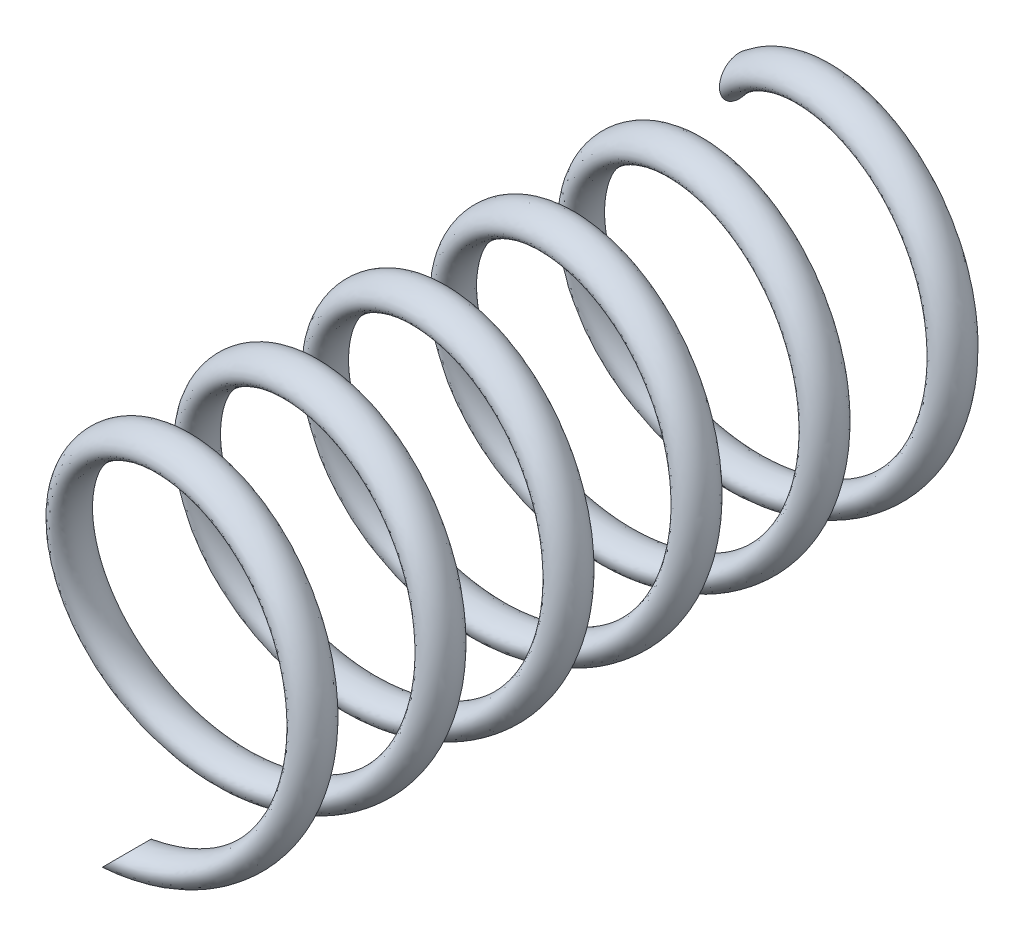
SolidWorks part; units mm, degrees
ref_plane "Front Plane" through (0, 0, 0) normal (0, 0, 1) x (1, 0, 0)
ref_plane "Top Plane" through (0, 0, 0) normal (0, 1, 0) x (1, 0, 0)
ref_plane "Right Plane" through (0, 0, 0) normal (1, 0, 0) x (0, 0, -1)
sketch "Sketch4" plane through (0, 0, 0) normal (0, 0, 1) x (1, 0, 0)
  circle A0 centre (0, 0) radius 9.5
  dimension "D1" = 19
curve "Helix/Spiral1" pitch 8 height 45 turns 5.625
ref_plane "Plane1" through (-6.7175, 0, 0) normal (1, 0, 0) x (0, 0, -1)
sketch "Sketch5" plane through (-6.7175, 0, 0) normal (1, 0, 0) x (0, 0, -1)
  circle A0 centre (0, 6.7175) radius 1.25
  spline S0 degree 3 poles (0, 6.7175) (-0.1656, 7.5913) (-0.5005, 9.0079) (-0.9999, 9.7466) (-1.5, 9.0055) (-2, 6.8924) (-2.5, 3.7302) (-3, 0) (-3.5, -3.7301) (-4, -6.8924) (-4.5, -9.0054) (-5, -9.7473) (-5.5, -9.0054) (-6, -6.8924) (-6.6667, -2.6761) (-7.3333, 2.6761) (-8, 6.8924) (-8.5, 9.0054) (-9, 9.7473) (-9.5, 9.0054) (-10, 6.8924) (-10.6667, 2.6761) (-11.3333, -2.6761) (-12, -6.8924) (-12.5, -9.0054) (-13, -9.7473) (-13.5, -9.0054) (-14, -6.8924) (-14.6667, -2.6761) (-15.3333, 2.6761) (-16, 6.8924) (-16.5, 9.0054) (-17, 9.7473) (-17.5, 9.0054) (-18, 6.8924) (-18.6667, 2.6761) (-19.3333, -2.6761) (-20, -6.8924) (-20.5, -9.0054) (-21, -9.7473) (-21.5, -9.0054) (-22, -6.8924) (-22.6667, -2.6761) (-23.3333, 2.6761) (-24, 6.8924) (-24.5, 9.0054) (-25, 9.7473) (-25.5, 9.0054) (-26, 6.8924) (-26.6667, 2.6761) (-27.3333, -2.6761) (-28, -6.8924) (-28.5, -9.0054) (-29, -9.7473) (-29.5, -9.0054) (-30, -6.8924) (-30.6667, -2.6761) (-31.3333, 2.6761) (-32, 6.8924) (-32.5, 9.0054) (-33, 9.7473) (-33.5, 9.0054) (-34, 6.8924) (-34.6667, 2.6761) (-35.3333, -2.6761) (-36, -6.8924) (-36.5, -9.0054) (-37, -9.7473) (-37.5, -9.0054) (-38, -6.8924) (-38.6667, -2.6761) (-39.3333, 2.6761) (-40, 6.8924) (-40.5, 9.0054) (-41, 9.7473) (-41.5, 9.0054) (-42, 6.8924) (-42.5, 3.7301) (-43, 0) (-43.5, -3.7301) (-44.0001, -6.8924) (-44.4995, -9.0054) (-44.8344, -9.5) (-45, -9.5) knots 0 0 0 0 0.011111 0.022222 0.033333 0.044444 0.055556 0.066667 0.077778 0.088889 0.1 0.111111 0.122222 0.133333 0.144444 0.166667 0.177778 0.188889 0.2 0.211111 0.222222 0.233333 0.255556 0.266667 0.277778 0.288889 0.3 0.311111 0.322222 0.344444 0.355556 0.366667 0.377778 0.388889 0.4 0.411111 0.433333 0.444444 0.455556 0.466667 0.477778 0.488889 0.5 0.522222 0.533333 0.544444 0.555556 0.566667 0.577778 0.588889 0.611111 0.622222 0.633333 0.644444 0.655556 0.666667 0.677778 0.7 0.711111 0.722222 0.733333 0.744444 0.755556 0.766667 0.788889 0.8 0.811111 0.822222 0.833333 0.844444 0.855556 0.877778 0.888889 0.9 0.911111 0.922222 0.933333 0.944444 0.955556 0.966667 0.977778 0.988889 1 1 1 1 construction
  dimension "D1" = 2.5
sweep "Sweep1" add profiles "Sketch5" path "Helix/Spiral1"
